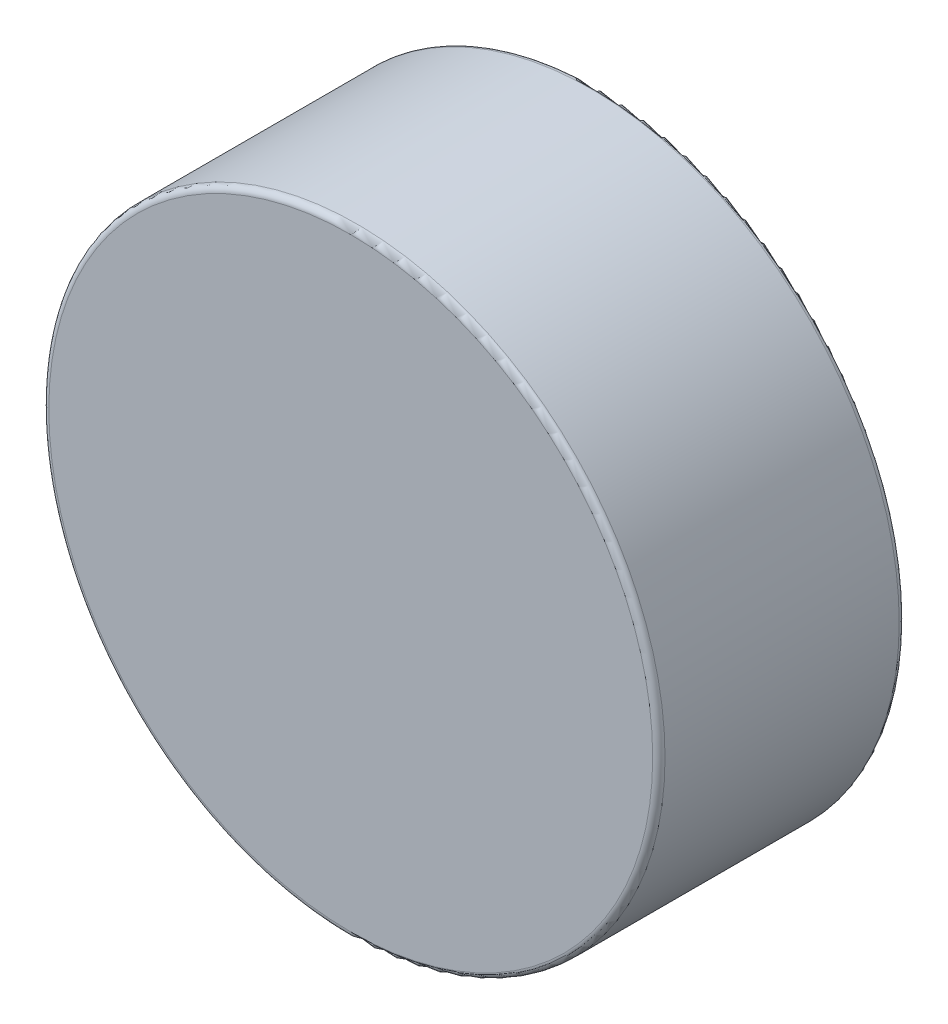
SolidWorks part; units mm, degrees
ref_plane "Front Plane" through (0, 0, 0) normal (0, 0, 1) x (1, 0, 0)
ref_plane "Top Plane" through (0, 0, 0) normal (0, 1, 0) x (1, 0, 0)
ref_plane "Right Plane" through (0, 0, 0) normal (1, 0, 0) x (0, 0, -1)
sketch "Sketch1" plane through (0, 0, 0) normal (0, 0, 1) x (1, 0, 0)
  circle A0 centre (0, 0) radius 3.9688 construction
  dimension "OD" = 7.9375
sketch "Sketch2" plane through (0, 0, 0) normal (1, 0, 0) x (0, 0, -1)
  line L0 (-1.5875, 0) -> (1.5875, 0) construction
  line L1 (0, 3.9688) -> (0, -3.9688) construction
  line L3 (-1.5875, 3.9688) -> (1.5875, 3.9688)
  line L4 (-1.5875, 3.9688) -> (-1.5875, -3.9688)
  line L5 (-1.5875, -3.9688) -> (1.5875, -3.9688)
  line L6 (1.5875, 3.9688) -> (1.5875, -3.9688)
  point P4 (0, 0)
  point P12 (0, 3.9688)
  dimension "Thickness" = 3.175
sketch "Sketch3" plane through (0, 0, 0) normal (0, 0, 1) x (1, 0, 0)
  circle A0 centre (0, 0) radius 3.9688 construction
  circle A1 centre (0, 0) radius 3.9688
extrude "Boss-Extrude1" add sketch "Sketch3" along normal up to vertex (1.5875 mm away) and the other way up to vertex (1.5875 mm away) up to point (0, 3.9688, 1.5875) other way up to point (0, 3.9688, -1.5875)
fillet "Fillet1" radius 0.0794 2 edges at (3.9688, 0, -1.5875) (3.9688, 0, 1.5875)
equation "\"Fillet@Fillet1\"=\"Thickness@Sketch2\"*.025"
